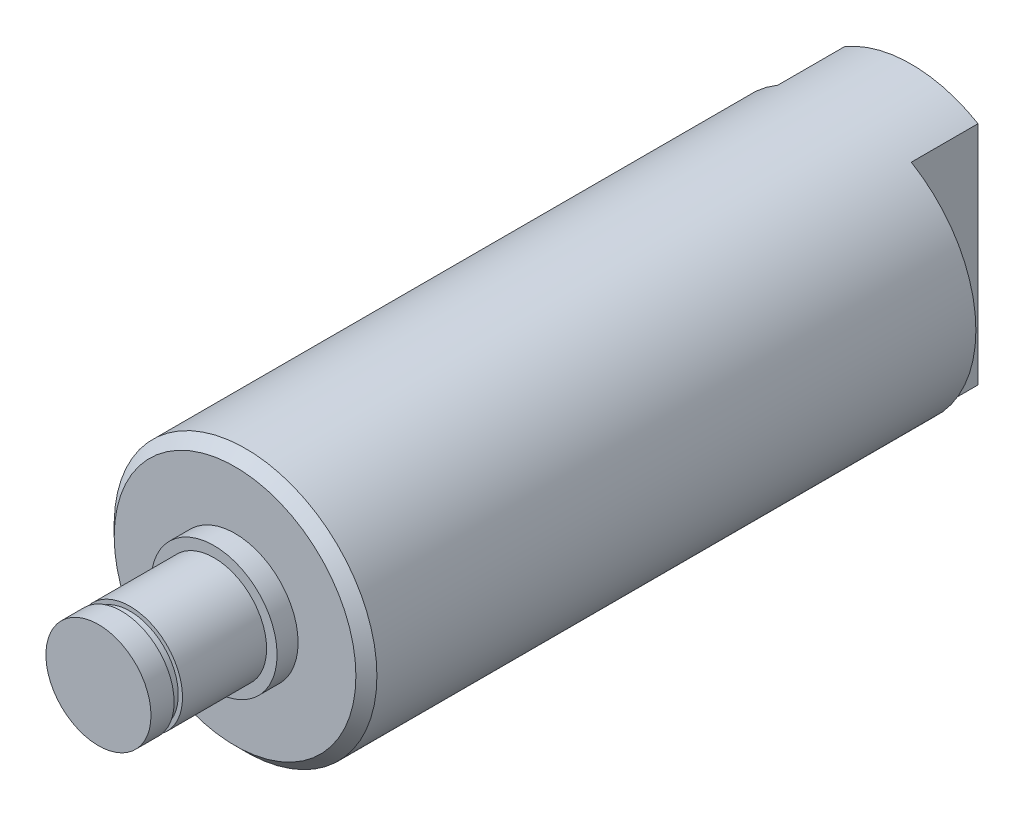
SolidWorks part; units mm, degrees
material "AISI 1020"
ref_plane "Alzado" through (0, 0, 0) normal (0, 0, 1) x (1, 0, 0)
ref_plane "Planta" through (0, 0, 0) normal (0, 1, 0) x (1, 0, 0)
ref_plane "Vista lateral" through (0, 0, 0) normal (1, 0, 0) x (0, 0, -1)
sketch "Croquis1" plane through (0, 0, 0) normal (0, 0, 1) x (1, 0, 0)
  circle A0 centre (0, 0) radius 6.35
  dimension "D1" = 12.7
extrude "Saliente-Extruir1" add sketch "Croquis1" along normal blind 6.35
sketch "Croquis2" plane through (0, 0, 6.35) normal (0, 0, 1) x (1, 0, 0)
  circle A0 centre (0, 0) radius 12.5
  dimension "D1" = 25
extrude "Saliente-Extruir2" add sketch "Croquis2" along normal blind 58
sketch "Croquis3" plane through (0, 0, 64.35) normal (0, 0, 1) x (1, 0, 0)
  circle A0 centre (0, 0) radius 6
  dimension "D1" = 12
extrude "Saliente-Extruir3" add sketch "Croquis3" along normal blind 2
sketch "Croquis4" plane through (0, 0, 66.35) normal (0, 0, 1) x (1, 0, 0)
  circle A0 centre (0, 0) radius 5
  dimension "D1" = 10
extrude "Saliente-Extruir4" add sketch "Croquis4" along normal blind 11
sketch "Croquis6" plane through (0, 0, 6.35) normal (0, 0, -1) x (-1, 0, 0)
  line L0 (-6.35, 10.767) -> (-6.35, -10.767)
  line L1 (6.35, 10.767) -> (6.35, -10.767)
  line L2 (-6.35, 0) -> (6.35, 0) construction
  circle A0 centre (0, 0) radius 12.5 construction
  arc A1 (6.35, 10.767) -> (-6.35, 10.767) centre (0, 0) ccw
  arc A2 (-6.35, -10.767) -> (6.35, -10.767) centre (0, 0) ccw
  point P8 (0, 0)
  dimension "D1" = 12.7
extrude "Saliente-Extruir5" add sketch "Croquis6" along normal blind 6.35
sketch "Croquis7" plane through (0, 0, 0) normal (1, 0, 0) x (0, 0, -1)
  line L0 (-66.35, 5) -> (-77.35, 5) construction
  line L1 (-75.15, 5.4) -> (-74.35, 5.4)
  line L2 (-75.15, 5.4) -> (-75.15, 4.6)
  line L3 (-75.15, 4.6) -> (-74.35, 4.6)
  line L4 (-74.35, 5.4) -> (-74.35, 4.6)
  line L5 (-75.15, 5.4) -> (-74.35, 4.6) construction
  line L6 (-75.15, 4.6) -> (-74.35, 5.4) construction
  line L7 (-66.35, 6) -> (-66.35, -6) construction
  line L8 (-66.35, 0) -> (-96.062, 0) construction
  point P0 (-74.75, 5)
  dimension "D1" = 8
  dimension "D2" = 0.8
revolve "Cortar-Revolución1" cut sketch "Croquis7" angle 360 about L8
chamfer "Chaflán1" distance 1 angle 45 1 edges at (12.5, 0, 64.35)
sketch "Croquis10" plane through (0, 0, 0) normal (0, 0, -1) x (-1, 0, 0)
  point P0 (0, 0)
hole_wizard "Taladro roscado M10x1.251" positions "Croquis11" profile "Croquis12" tap size "M10x1.25" standard "Ansi Metric"
sketch "Croquis11" plane through (0, 0, 0) normal (0, 0, -1) x (-1, 0, 0)
  point P0 (0, 0)
sketch "Croquis12" plane through (0, 0, 0) normal (1, 0, 0) x (0, 1, 0)
  line L0 (0, 0) -> (0, 27.6438)
  line L1 (0, 27.6438) -> (4.4, 25)
  line L2 (4.4, 25) -> (4.4, 0)
  line L5 (4.4, 0) -> (0, 0)
  line L10 (0, 27.6438) -> (-4.4, 25) construction
  line L11 (0, -6.35) -> (0, 107.95) construction
  dimension "Diámetro de perforador para roscar" = 8.8
  dimension "Profundidad de perforador para roscar" = 25
  dimension "Ángulo de perforador" = 118
cosmetic thread "Rosca de taladro1" parameters "D1"=20, "D2"=10
